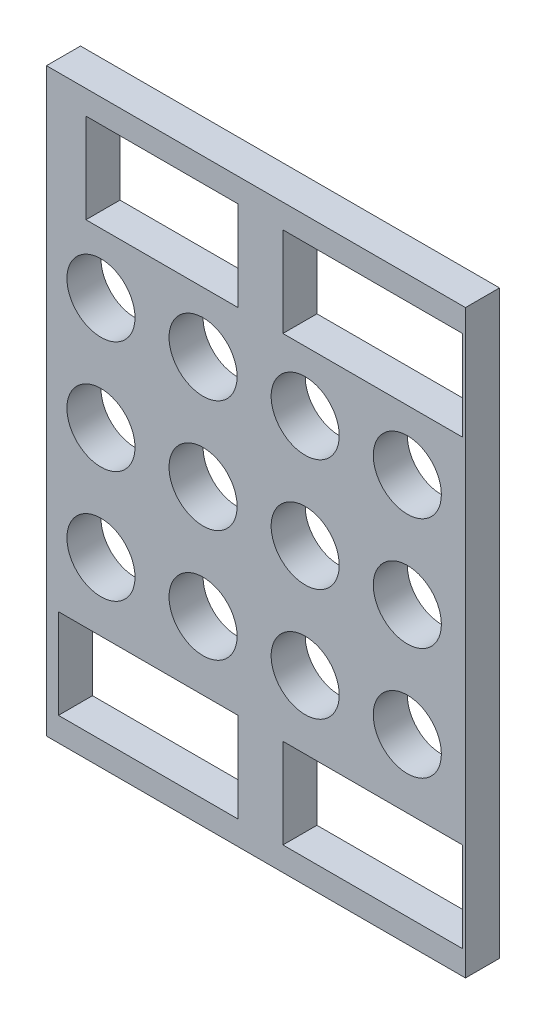
SolidWorks part; units mm, degrees
ref_plane "Front Plane" through (0, 0, 0) normal (0, 0, 1) x (1, 0, 0)
ref_plane "Top Plane" through (0, 0, 0) normal (0, 1, 0) x (1, 0, 0)
ref_plane "Right Plane" through (0, 0, 0) normal (1, 0, 0) x (0, 0, -1)
sketch "Sketch1" plane through (0, 0, 0) normal (0, 0, 1) x (1, 0, 0)
  line L0 (223.4691, 434.1047) -> (223.4691, 348.8243)
  line L1 (223.4691, 348.8243) -> (285.0116, 348.8243)
  line L2 (285.0116, 348.8243) -> (285.0116, 434.1047)
  line L3 (285.0116, 434.1047) -> (223.4691, 434.1047)
  line L5 (229.2656, 430.588) -> (251.6028, 430.588)
  line L6 (229.2656, 430.588) -> (229.2656, 417.4003)
  line L7 (229.2656, 417.4003) -> (251.6028, 417.4003)
  line L8 (251.6028, 430.588) -> (251.6028, 417.4003)
  line L9 (258.1967, 430.588) -> (284.572, 430.588)
  line L10 (258.1967, 430.588) -> (258.1967, 417.4003)
  line L11 (258.1967, 417.4003) -> (284.572, 417.4003)
  line L12 (284.572, 430.588) -> (284.572, 417.4003)
  line L13 (225.2274, 365.5287) -> (251.6028, 365.5287)
  line L14 (225.2274, 365.5287) -> (225.2274, 352.341)
  line L15 (225.2274, 352.341) -> (251.6028, 352.341)
  line L16 (251.6028, 365.5287) -> (251.6028, 352.341)
  line L17 (258.1967, 365.5287) -> (284.572, 365.5287)
  line L18 (258.1967, 365.5287) -> (258.1967, 352.341)
  line L19 (258.1967, 352.341) -> (284.572, 352.341)
  line L20 (284.572, 365.5287) -> (284.572, 352.341)
  circle A0 centre (231.4691, 408.546) radius 5
  circle A1 centre (246.4691, 408.546) radius 5
  circle A2 centre (261.4691, 408.546) radius 5
  circle A3 centre (276.4691, 408.546) radius 5
  circle A4 centre (231.4691, 392.046) radius 5
  circle A5 centre (246.4691, 392.046) radius 5
  circle A6 centre (261.4691, 392.046) radius 5
  circle A7 centre (276.4691, 392.046) radius 5
  circle A8 centre (231.4691, 375.546) radius 5
  circle A9 centre (246.4691, 375.546) radius 5
  circle A10 centre (261.4691, 375.546) radius 5
  circle A11 centre (276.4691, 375.546) radius 5
  dimension "D1" = 10
  dimension "D2" = 10
  dimension "D3" = 10
  dimension "D4" = 10
  dimension "D5" = 15
  dimension "D6" = 15
  dimension "D7" = 15
  dimension "D8" = 8
  dimension "D9" = 3
extrude "Boss-Extrude1" add sketch "Sketch1" along normal blind 5
